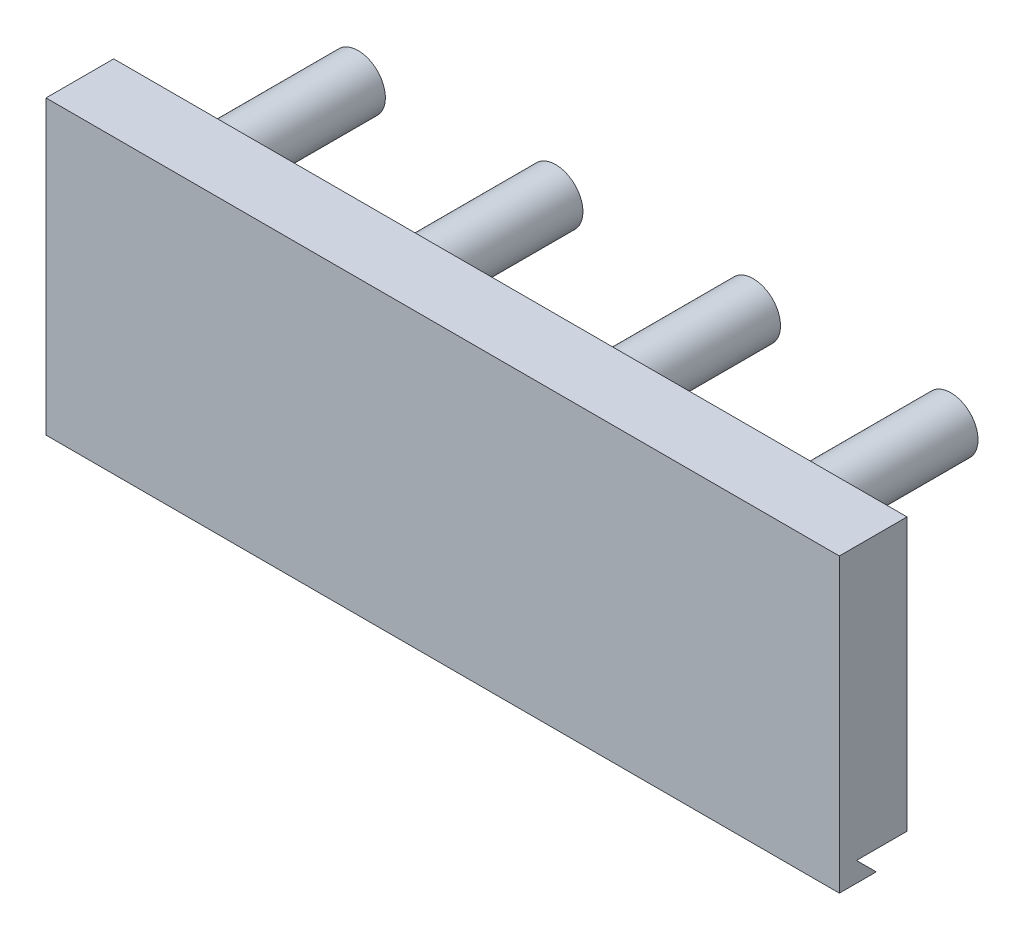
SolidWorks part; units mm, degrees
ref_plane "Front Plane" through (0, 0, 0) normal (0, 0, 1) x (1, 0, 0)
ref_plane "Top Plane" through (0, 0, 0) normal (0, 1, 0) x (1, 0, 0)
ref_plane "Right Plane" through (0, 0, 0) normal (1, 0, 0) x (0, 0, -1)
sketch "Sketch1" plane through (0, 0, 0) normal (0, 0, 1) x (1, 0, 0)
  line L1 (-51, -17.5) -> (51, -17.5)
  line L2 (-51, -17.5) -> (-51, 17.5)
  line L3 (-51, 17.5) -> (51, 17.5)
  line L4 (51, -17.5) -> (51, 17.5)
  line L5 (-51, -17.5) -> (51, 17.5) construction
  line L6 (-51, 17.5) -> (51, -17.5) construction
  point P0 (0, 0)
  dimension "D1" = 35
  dimension "D2" = 102
extrude "Boss-Extrude1" add sketch "Sketch1" along normal blind 8.7
sketch "Sketch4" plane through (-51, 0, 0) normal (-1, 0, 0) x (0, 0, 1)
  line L2 (6.5, -17.5) -> (8.7, -17.5)
  line L6 (8.7, -17.5) -> (8.7, -20.0456)
  line L12 (8.7, -20.0456) -> (3.9544, -20.0456)
  line L13 (3.9544, -20.0456) -> (6.5, -17.5)
  line L14 (8.7, -17.5) -> (0, -17.5) construction
  dimension "D1" = 6.5
  dimension "D2" = 45
  dimension "D3" = 3.6
extrude "Boss-Extrude2" add sketch "Sketch4" against normal blind 102
sketch "Sketch5" plane through (0, 0, 0) normal (0, 0, -1) x (-1, 0, 0)
  line L0 (51, -17.5) -> (-51, -17.5) construction
  line L1 (-51, -17.5) -> (-51, 17.5) construction
  circle A0 centre (-36.63, 10.64) radius 3.5
  circle A1 centre (-11.23, 10.64) radius 3.5
  circle A2 centre (14.17, 10.64) radius 3.5
  circle A3 centre (39.57, 10.64) radius 3.5
  dimension "D2" = 7
  dimension "D7" = 7
  dimension "D8" = 7
  dimension "D9" = 7
  dimension "D1" = 28.14
  dimension "D3" = 14.37
  dimension "D4" = 25.4
  dimension "D5" = 25.4
  dimension "D6" = 25.4
  dimension "D10" = 28.14
  dimension "D11" = 28.14
  dimension "D12" = 28.14
extrude "Boss-Extrude3" add sketch "Sketch5" along normal blind 20
